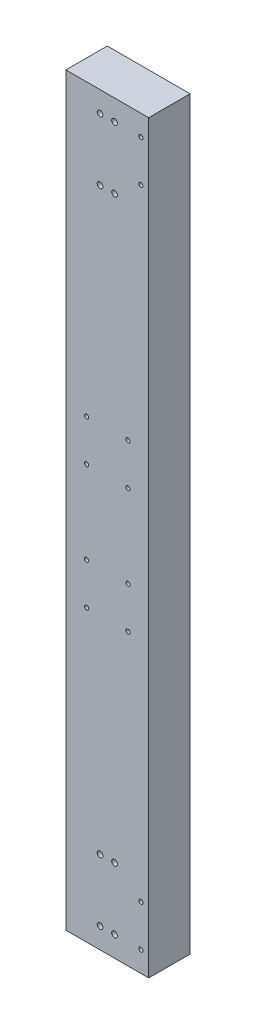
SolidWorks part; units mm, degrees
ref_plane "Front Plane" through (0, 0, 0) normal (0, 0, 1) x (1, 0, 0)
ref_plane "Top Plane" through (0, 0, 0) normal (0, 1, 0) x (1, 0, 0)
ref_plane "Right Plane" through (0, 0, 0) normal (1, 0, 0) x (0, 0, -1)
sketch "Sketch1" plane through (0, 0, 0) normal (0, 1, 0) x (1, 0, 0)
  line L1 (-50.8, 25.4) -> (50.8, 25.4)
  line L2 (-50.8, 25.4) -> (-50.8, -25.4)
  line L3 (-50.8, -25.4) -> (50.8, -25.4)
  line L4 (50.8, 25.4) -> (50.8, -25.4)
  line L5 (-50.8, 25.4) -> (50.8, -25.4) construction
  line L6 (-50.8, -25.4) -> (50.8, 25.4) construction
  point P0 (0, 0)
  dimension "D1" = 50.8
  dimension "D2" = 101.6
extrude "Boss-Extrude1" add sketch "Sketch1" along normal blind 914.4
ref_plane "Plane1" through (0, 457.2, 0) normal (0, 1, 0) x (1, 0, 0)
sketch "Sketch3" plane through (0, 0, -25.4) normal (0, 0, -1) x (-1, 0, 0)
  line L0 (-50.8, 0) -> (50.8, 0) construction
  line L1 (-8.89, 101.6) -> (8.89, 101.6) construction
  line L2 (-8.89, 101.6) -> (-8.89, 25.4) construction
  line L3 (-8.89, 25.4) -> (8.89, 25.4) construction
  line L4 (8.89, 101.6) -> (8.89, 25.4) construction
  line L5 (-8.89, 101.6) -> (8.89, 25.4) construction
  line L6 (-8.89, 25.4) -> (8.89, 101.6) construction
  circle A0 centre (-8.89, 25.4) radius 3.4925
  circle A1 centre (8.89, 25.4) radius 3.4925
  circle A2 centre (8.89, 101.6) radius 3.4925
  circle A3 centre (-8.89, 101.6) radius 3.4925
  point P0 (0, 63.5)
  dimension "D4" = 6.985
  dimension "D1" = 76.2
  dimension "D2" = 17.78
  dimension "D3" = 25.4
extrude "Cut-Extrude1" cut sketch "Sketch3" against normal up to surface (50.8 mm away) up to face at (0, 457.2, 25.4)
sketch "Sketch4" plane through (0, 0, -25.4) normal (0, 0, -1) x (-1, 0, 0)
  line L0 (-50.8, 0) -> (50.8, 0) construction
  line L1 (-50.8, 914.4) -> (-50.8, 0) construction
  circle A0 centre (-41.275, 76.2) radius 2.5527
  circle A1 centre (-41.275, 25.4) radius 2.5527
  dimension "D1" = 5.1054
  dimension "D2" = 25.4
  dimension "D3" = 50.8
  dimension "D4" = 9.525
extrude "Cut-Extrude2" cut sketch "Sketch4" against normal up to surface (50.8 mm away) up to face at (5.3975, 25.4, 25.4)
mirror "Mirror1" about plane through (0, 457.2, 0) normal (0, 1, 0) of "Cut-Extrude2", "Cut-Extrude1"
sketch "Sketch5" plane through (0, 0, -25.4) normal (0, 0, -1) x (-1, 0, 0)
  line L0 (27.94, 457.2) -> (-27.94, 457.2) construction
  line L1 (-25.4, 406.4) -> (25.4, 406.4) construction
  line L2 (-25.4, 406.4) -> (-25.4, 355.6) construction
  line L3 (-25.4, 355.6) -> (25.4, 355.6) construction
  line L4 (25.4, 406.4) -> (25.4, 355.6) construction
  line L5 (-25.4, 406.4) -> (25.4, 355.6) construction
  line L6 (-25.4, 355.6) -> (25.4, 406.4) construction
  circle A0 centre (-25.4, 406.4) radius 2.5527
  circle A1 centre (25.4, 406.4) radius 2.5527
  circle A2 centre (25.4, 355.6) radius 2.5527
  circle A3 centre (-25.4, 355.6) radius 2.5527
  point P0 (0, 381)
  dimension "D4" = 5.1054
  dimension "D1" = 50.8
  dimension "D2" = 50.8
  dimension "D3" = 50.8
extrude "Cut-Extrude3" cut sketch "Sketch5" against normal up to surface (50.8 mm away) up to face at (38.7223, 838.2, 25.4)
mirror "Mirror2" about plane through (0, 457.2, 0) normal (0, 1, 0) of "Cut-Extrude3"
